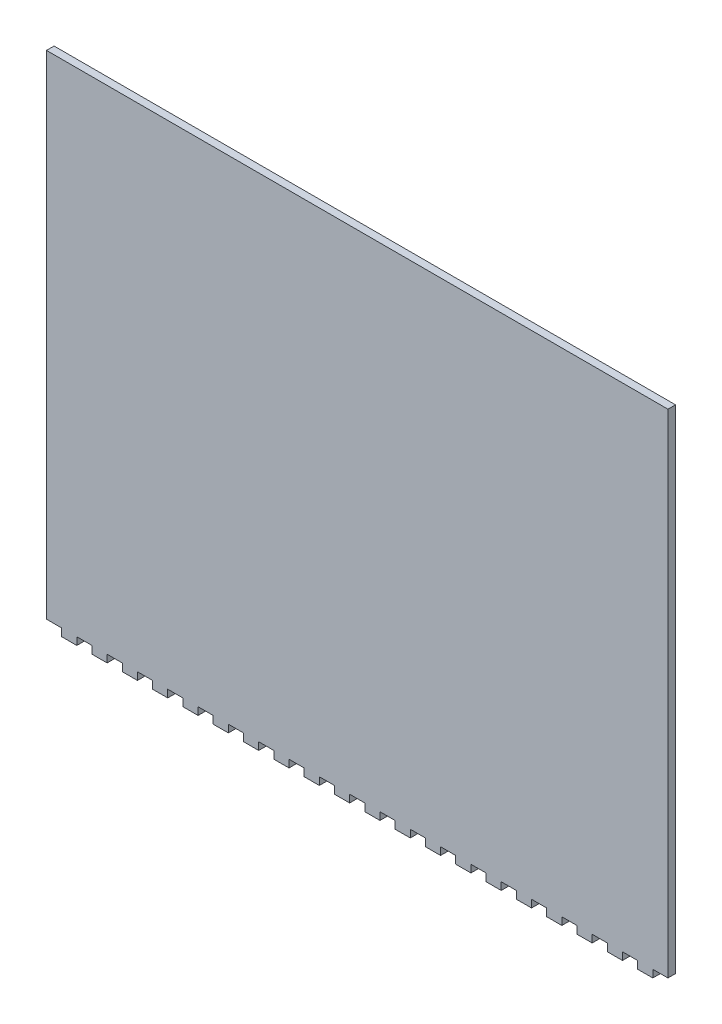
SolidWorks part; units mm, degrees
ref_plane "Plan de face" through (0, 0, 0) normal (0, 0, 1) x (1, 0, 0)
ref_plane "Plan de dessus" through (0, 0, 0) normal (0, 1, 0) x (1, 0, 0)
ref_plane "Plan de droite" through (0, 0, 0) normal (1, 0, 0) x (0, 0, -1)
sketch "Esquisse1" plane through (0, 0, 0) normal (0, 0, 1) x (1, 0, 0)
  line L1 (0, 0) -> (410, 0)
  line L2 (0, 0) -> (0, 330)
  line L3 (0, 330) -> (410, 330)
  line L4 (410, 0) -> (410, 330)
  dimension "D1" = 330
  dimension "D2" = 410
extrude "Boss.-Extru.1" add sketch "Esquisse1" along normal blind 5 contours L2 L3 L4 L1
sketch "Esquisse2" plane through (0, 0, 5) normal (0, 0, 1) x (1, 0, 0)
  line L0 (20, 0) -> (20, 5)
  line L1 (0, 0) -> (10, 0)
  line L2 (0, 0) -> (0, 5)
  line L3 (0, 5) -> (10, 5)
  line L4 (10, 0) -> (10, 5)
  line L5 (20, 0) -> (30, 0)
  line L6 (30, 0) -> (30, 5)
  line L7 (20, 5) -> (30, 5)
  line L8 (40, 0) -> (40, 5)
  line L9 (40, 0) -> (50, 0)
  line L10 (50, 0) -> (50, 5)
  line L11 (40, 5) -> (50, 5)
  line L12 (60, 0) -> (60, 5)
  line L13 (60, 0) -> (70, 0)
  line L14 (70, 0) -> (70, 5)
  line L15 (60, 5) -> (70, 5)
  line L16 (80, 0) -> (80, 5)
  line L17 (80, 0) -> (90, 0)
  line L18 (90, 0) -> (90, 5)
  line L19 (80, 5) -> (90, 5)
  line L20 (100, 0) -> (100, 5)
  line L21 (100, 0) -> (110, 0)
  line L22 (110, 0) -> (110, 5)
  line L23 (100, 5) -> (110, 5)
  line L24 (120, 0) -> (120, 5)
  line L25 (120, 0) -> (130, 0)
  line L26 (130, 0) -> (130, 5)
  line L27 (120, 5) -> (130, 5)
  line L28 (140, 0) -> (140, 5)
  line L29 (140, 0) -> (150, 0)
  line L30 (150, 0) -> (150, 5)
  line L31 (140, 5) -> (150, 5)
  line L32 (160, 0) -> (160, 5)
  line L33 (160, 0) -> (170, 0)
  line L34 (170, 0) -> (170, 5)
  line L35 (160, 5) -> (170, 5)
  line L36 (180, 0) -> (180, 5)
  line L37 (180, 0) -> (190, 0)
  line L38 (190, 0) -> (190, 5)
  line L39 (180, 5) -> (190, 5)
  line L40 (200, 0) -> (200, 5)
  line L41 (200, 0) -> (210, 0)
  line L42 (210, 0) -> (210, 5)
  line L43 (200, 5) -> (210, 5)
  line L44 (220, 0) -> (220, 5)
  line L45 (220, 0) -> (230, 0)
  line L46 (230, 0) -> (230, 5)
  line L47 (220, 5) -> (230, 5)
  line L48 (240, 0) -> (240, 5)
  line L49 (240, 0) -> (250, 0)
  line L50 (250, 0) -> (250, 5)
  line L51 (240, 5) -> (250, 5)
  line L52 (260, 0) -> (260, 5)
  line L53 (260, 0) -> (270, 0)
  line L54 (270, 0) -> (270, 5)
  line L55 (260, 5) -> (270, 5)
  line L56 (280, 0) -> (280, 5)
  line L57 (280, 0) -> (290, 0)
  line L58 (290, 0) -> (290, 5)
  line L59 (280, 5) -> (290, 5)
  line L60 (300, 0) -> (300, 5)
  line L61 (300, 0) -> (310, 0)
  line L62 (310, 0) -> (310, 5)
  line L63 (300, 5) -> (310, 5)
  line L64 (320, 0) -> (320, 5)
  line L65 (320, 0) -> (330, 0)
  line L66 (330, 0) -> (330, 5)
  line L67 (320, 5) -> (330, 5)
  line L68 (340, 0) -> (340, 5)
  line L69 (340, 0) -> (350, 0)
  line L70 (350, 0) -> (350, 5)
  line L71 (340, 5) -> (350, 5)
  line L72 (360, 0) -> (360, 5)
  line L73 (360, 0) -> (370, 0)
  line L74 (370, 0) -> (370, 5)
  line L75 (360, 5) -> (370, 5)
  line L76 (380, 0) -> (380, 5)
  line L77 (380, 0) -> (390, 0)
  line L78 (390, 0) -> (390, 5)
  line L79 (380, 5) -> (390, 5)
  line L80 (400, 0) -> (400, 5)
  line L81 (400, 0) -> (410, 0)
  line L82 (410, 0) -> (410, 5)
  line L83 (400, 5) -> (410, 5)
  dimension "D1" = 10
  dimension "D2" = 5
  dimension "D3" = 21
extrude "Enlèv. mat.-Extru.1" cut sketch "Esquisse2" against normal through all
